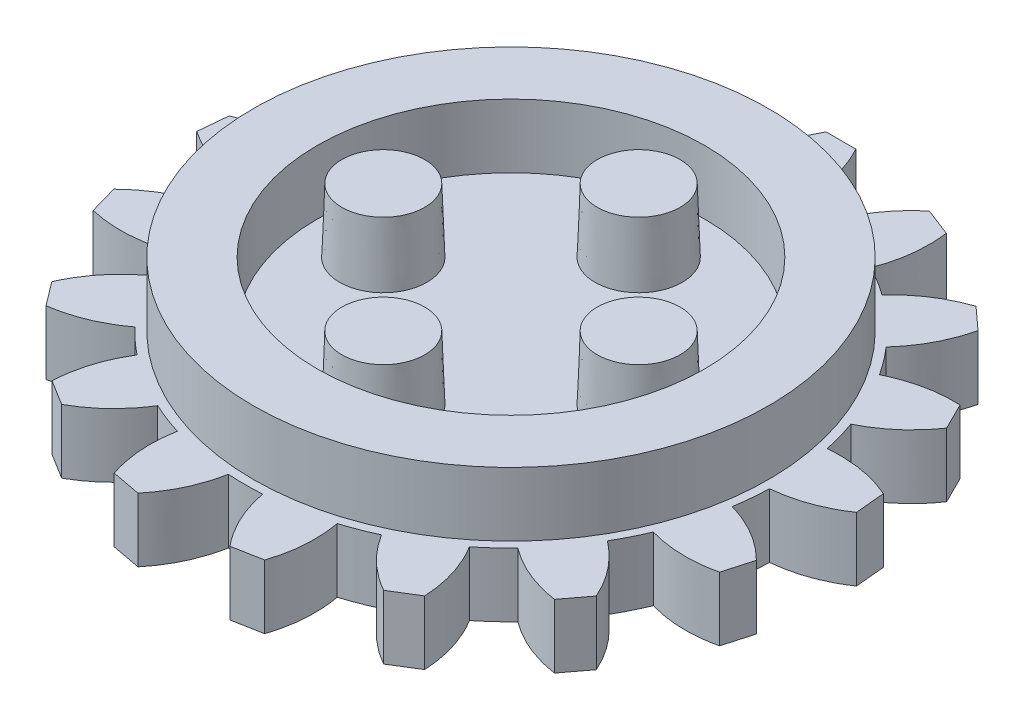
SolidWorks part; units mm, degrees
ref_plane "Front Plane" through (0, 0, 0) normal (0, 0, 1) x (1, 0, 0)
ref_plane "Top Plane" through (0, 0, 0) normal (0, 1, 0) x (1, 0, 0)
ref_plane "Right Plane" through (0, 0, 0) normal (1, 0, 0) x (0, 0, -1)
sketch "Sketch2" plane through (0, 0, 0) normal (0, 1, 0) x (1, 0, 0)
  line L0 (0, 12.5) -> (0, 15.5) construction
  line L1 (0, 14) -> (1.3, 14) construction
  line L2 (-0.7, 15.5) -> (0.7, 15.5)
  line L3 (4.9465, 14.7062) -> (6.252, 14.2005)
  line L4 (9.925, 11.9262) -> (10.9596, 10.9831)
  line L5 (13.563, 7.5356) -> (14.187, 6.2823)
  line L6 (15.3693, 2.1272) -> (15.4985, 0.7331)
  line L7 (15.0999, -3.5685) -> (14.7167, -4.9151)
  line L8 (12.7911, -8.7822) -> (11.9474, -9.8994)
  line L9 (8.7549, -12.8099) -> (7.5645, -13.5469)
  line L10 (3.5362, -15.1075) -> (2.16, -15.3647)
  line L11 (-2.16, -15.3647) -> (-3.5362, -15.1075)
  line L12 (-7.5645, -13.5469) -> (-8.7549, -12.8099)
  line L13 (-11.9474, -9.8994) -> (-12.7911, -8.7822)
  line L14 (-14.7167, -4.9151) -> (-15.0999, -3.5685)
  line L15 (-15.4985, 0.7331) -> (-15.3693, 2.1272)
  line L16 (-14.187, 6.2823) -> (-13.563, 7.5356)
  line L17 (-10.9596, 10.9831) -> (-9.925, 11.9262)
  line L18 (-6.252, 14.2005) -> (-4.9465, 14.7062)
  circle A0 centre (0, 0) radius 8.9
  circle A1 centre (0, 0) radius 12.5 construction
  arc A2 (1.5, 12.4097) -> (3.0842, 12.1135) centre (0, 0) cw
  arc A3 (5.8816, 11.0298) -> (7.2518, 10.1814) centre (0, 0) cw
  arc A4 (9.4689, 8.1603) -> (10.4401, 6.8742) centre (0, 0) cw
  arc A5 (11.7773, 4.1887) -> (12.2183, 2.6386) centre (0, 0) cw
  arc A6 (12.4951, -0.3486) -> (12.3464, -1.9533) centre (0, 0) cw
  arc A7 (11.5254, -4.8388) -> (10.8071, -6.2815) centre (0, 0) cw
  arc A8 (8.9992, -8.6755) -> (7.8082, -9.7613) centre (0, 0) cw
  arc A9 (5.2575, -11.3406) -> (3.7547, -11.9228) centre (0, 0) cw
  arc A10 (0.8058, -12.474) -> (-0.8058, -12.474) centre (0, 0) cw
  arc A11 (-3.7547, -11.9228) -> (-5.2575, -11.3406) centre (0, 0) cw
  arc A12 (-7.8082, -9.7613) -> (-8.9992, -8.6755) centre (0, 0) cw
  arc A13 (-10.8071, -6.2815) -> (-11.5254, -4.8388) centre (0, 0) cw
  arc A14 (-12.3464, -1.9533) -> (-12.4951, -0.3486) centre (0, 0) cw
  arc A15 (-12.2183, 2.6386) -> (-11.7773, 4.1887) centre (0, 0) cw
  arc A16 (-10.4401, 6.8742) -> (-9.4689, 8.1603) centre (0, 0) cw
  arc A17 (-7.2518, 10.1814) -> (-5.8816, 11.0298) centre (0, 0) cw
  arc A18 (-3.0842, 12.1135) -> (-1.5, 12.4097) centre (0, 0) cw
  spline S0 degree 2 poles (0.7, 15.5) (1.4969, 14.0574) (1.5, 12.4097) knots 0 0 0 1 1 1
  spline S1 degree 2 poles (-0.7, 15.5) (-1.4969, 14.0574) (-1.5, 12.4097) knots 0 0 0 1 1 1
  spline S2 degree 2 poles (6.252, 14.2005) (6.4739, 12.5674) (5.8816, 11.0298) knots 0 0 0 1 1 1
  spline S3 degree 2 poles (4.9465, 14.7062) (3.6823, 13.6488) (3.0842, 12.1135) knots 0 0 0 1 1 1
  spline S4 degree 2 poles (10.9596, 10.9831) (10.5766, 9.3801) (9.4689, 8.1603) knots 0 0 0 1 1 1
  spline S5 degree 2 poles (9.925, 11.9262) (8.3642, 11.3969) (7.2518, 10.1814) knots 0 0 0 1 1 1
  spline S6 degree 2 poles (14.187, 6.2823) (13.2508, 4.926) (11.7773, 4.1887) knots 0 0 0 1 1 1
  spline S7 degree 2 poles (13.563, 7.5356) (11.9164, 7.6058) (10.4401, 6.8742) knots 0 0 0 1 1 1
  spline S8 degree 2 poles (15.4985, 0.7331) (14.1355, -0.1934) (12.4951, -0.3486) knots 0 0 0 1 1 1
  spline S9 degree 2 poles (15.3693, 2.1272) (13.8593, 2.7875) (12.2183, 2.6386) knots 0 0 0 1 1 1
  spline S10 degree 2 poles (14.7167, -4.9151) (13.1111, -5.2867) (11.5254, -4.8388) knots 0 0 0 1 1 1
  spline S11 degree 2 poles (15.0999, -3.5685) (13.9304, -2.4073) (12.3464, -1.9533) knots 0 0 0 1 1 1
  spline S12 degree 2 poles (11.9474, -9.8994) (10.316, -9.666) (8.9992, -8.6755) knots 0 0 0 1 1 1
  spline S13 degree 2 poles (12.7911, -8.7822) (12.1201, -7.2769) (10.8071, -6.2815) knots 0 0 0 1 1 1
  spline S14 degree 2 poles (7.5645, -13.5469) (6.1276, -12.7398) (5.2575, -11.3406) knots 0 0 0 1 1 1
  spline S15 degree 2 poles (8.7549, -12.8099) (8.6729, -11.1638) (7.8082, -9.7613) knots 0 0 0 1 1 1
  spline S16 degree 2 poles (2.16, -15.3647) (1.1117, -14.093) (0.8058, -12.474) knots 0 0 0 1 1 1
  spline S17 degree 2 poles (3.5362, -15.1075) (4.0544, -13.543) (3.7547, -11.9228) knots 0 0 0 1 1 1
  spline S18 degree 2 poles (-3.5362, -15.1075) (-4.0544, -13.543) (-3.7547, -11.9228) knots 0 0 0 1 1 1
  spline S19 degree 2 poles (-2.16, -15.3647) (-1.1117, -14.093) (-0.8058, -12.474) knots 0 0 0 1 1 1
  spline S20 degree 2 poles (-8.7549, -12.8099) (-8.6729, -11.1638) (-7.8082, -9.7613) knots 0 0 0 1 1 1
  spline S21 degree 2 poles (-7.5645, -13.5469) (-6.1276, -12.7398) (-5.2575, -11.3406) knots 0 0 0 1 1 1
  spline S22 degree 2 poles (-12.7911, -8.7822) (-12.1201, -7.2769) (-10.8071, -6.2815) knots 0 0 0 1 1 1
  spline S23 degree 2 poles (-11.9474, -9.8994) (-10.316, -9.666) (-8.9992, -8.6755) knots 0 0 0 1 1 1
  spline S24 degree 2 poles (-15.0999, -3.5685) (-13.9304, -2.4073) (-12.3464, -1.9533) knots 0 0 0 1 1 1
  spline S25 degree 2 poles (-14.7167, -4.9151) (-13.1111, -5.2867) (-11.5254, -4.8388) knots 0 0 0 1 1 1
  spline S26 degree 2 poles (-15.3693, 2.1272) (-13.8593, 2.7875) (-12.2183, 2.6386) knots 0 0 0 1 1 1
  spline S27 degree 2 poles (-15.4985, 0.7331) (-14.1355, -0.1934) (-12.4951, -0.3486) knots 0 0 0 1 1 1
  spline S28 degree 2 poles (-13.563, 7.5356) (-11.9164, 7.6058) (-10.4401, 6.8742) knots 0 0 0 1 1 1
  spline S29 degree 2 poles (-14.187, 6.2823) (-13.2508, 4.926) (-11.7773, 4.1887) knots 0 0 0 1 1 1
  spline S30 degree 2 poles (-9.925, 11.9262) (-8.3642, 11.3969) (-7.2518, 10.1814) knots 0 0 0 1 1 1
  spline S31 degree 2 poles (-10.9596, 10.9831) (-10.5766, 9.3801) (-9.4689, 8.1603) knots 0 0 0 1 1 1
  spline S32 degree 2 poles (-4.9465, 14.7062) (-3.6823, 13.6488) (-3.0842, 12.1135) knots 0 0 0 1 1 1
  spline S33 degree 2 poles (-6.252, 14.2005) (-6.4739, 12.5674) (-5.8816, 11.0298) knots 0 0 0 1 1 1
  point P113 (0, 0)
  point P146 (0, 0)
  dimension "D1" = 17.8
  dimension "D5" = 25
  dimension "D2" = 0.7
  dimension "D3" = 1.5
  dimension "D4" = 1.3
  dimension "D6" = 3
  dimension "D7" = 17
  dimension "D8" = 17
extrude "Boss-Extrude1" add sketch "Sketch2" along normal mid plane 3
sketch "Sketch3" plane through (0, 1.5, 0) normal (0, 1, 0) x (1, 0, 0)
  circle A0 centre (0, 0) radius 9.1
  circle A1 centre (0, 0) radius 12.1
  dimension "D1" = 18.2
  dimension "D2" = 3
extrude "Boss-Extrude2" add sketch "Sketch3" along normal blind 3
sketch "Sketch4" plane through (0, -1.5, 0) normal (0, -1, 0) x (1, 0, 0)
  circle A0 centre (0, 0) radius 8.9 construction
  circle A1 centre (0, 0) radius 8.9
extrude "Boss-Extrude3" add sketch "Sketch4" against normal up to surface (3 mm away) up to face at (0, 1.5, 12.1)
sketch "Sketch5" plane through (0, 1.5, 0) normal (0, 1, 0) x (1, 0, 0)
  line L0 (6, 0) -> (-6, 0) construction
  line L1 (0, 0) -> (0, 9.1) construction
  circle A0 centre (-6, 0) radius 2.05
  circle A1 centre (0, 0) radius 9.1 construction
  circle A2 centre (6, 0) radius 2.05
  circle A3 centre (0, -6) radius 2.05
  circle A5 centre (0, 6) radius 2.05
  circle A6 centre (-6, 0) radius 2.05 [skipped]
  point P4 (0, 0)
  point P12 (1.604, 6.2906)
  point P13 (0, 0)
  point P21 (0, 0)
  dimension "D1" = 4.1
  dimension "D2" = 12
  dimension "D3" = 4
extrude "Boss-Extrude4" add sketch "Sketch5" along normal blind 3 draft 2
